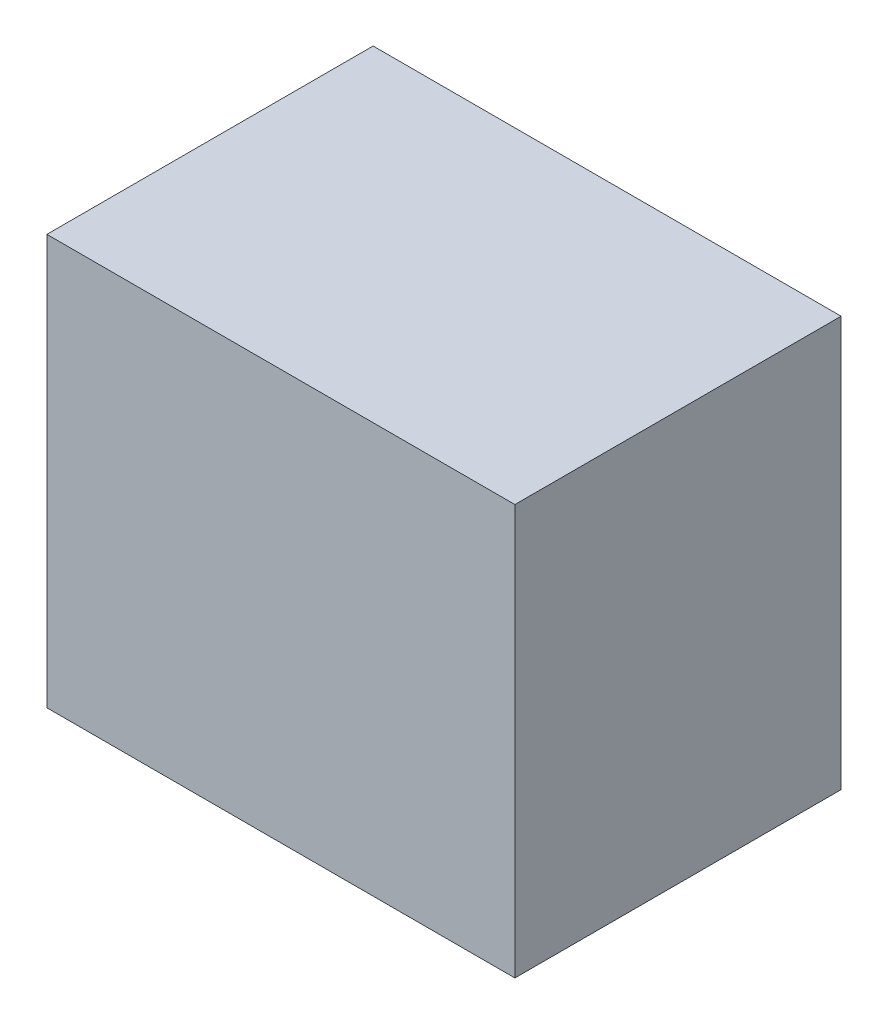
SolidWorks part; units mm, degrees
ref_plane "Front" through (0, 0, 0) normal (0, 0, 1) x (1, 0, 0)
ref_plane "Top" through (0, 0, 0) normal (0, 1, 0) x (1, 0, 0)
ref_plane "Right" through (0, 0, 0) normal (1, 0, 0) x (0, 0, -1)
sketch "Sketch1" plane through (0, 0, 0) normal (0, 0, 1) x (1, 0, 0)
  line L1 (0, 0) -> (28.7862, 0)
  line L2 (0, 0) -> (0, 25.221)
  line L3 (0, 25.221) -> (28.7862, 25.221)
  line L4 (28.7862, 0) -> (28.7862, 25.221)
extrude "Boss-Extrude1" add sketch "Sketch1" along normal blind 20.066
